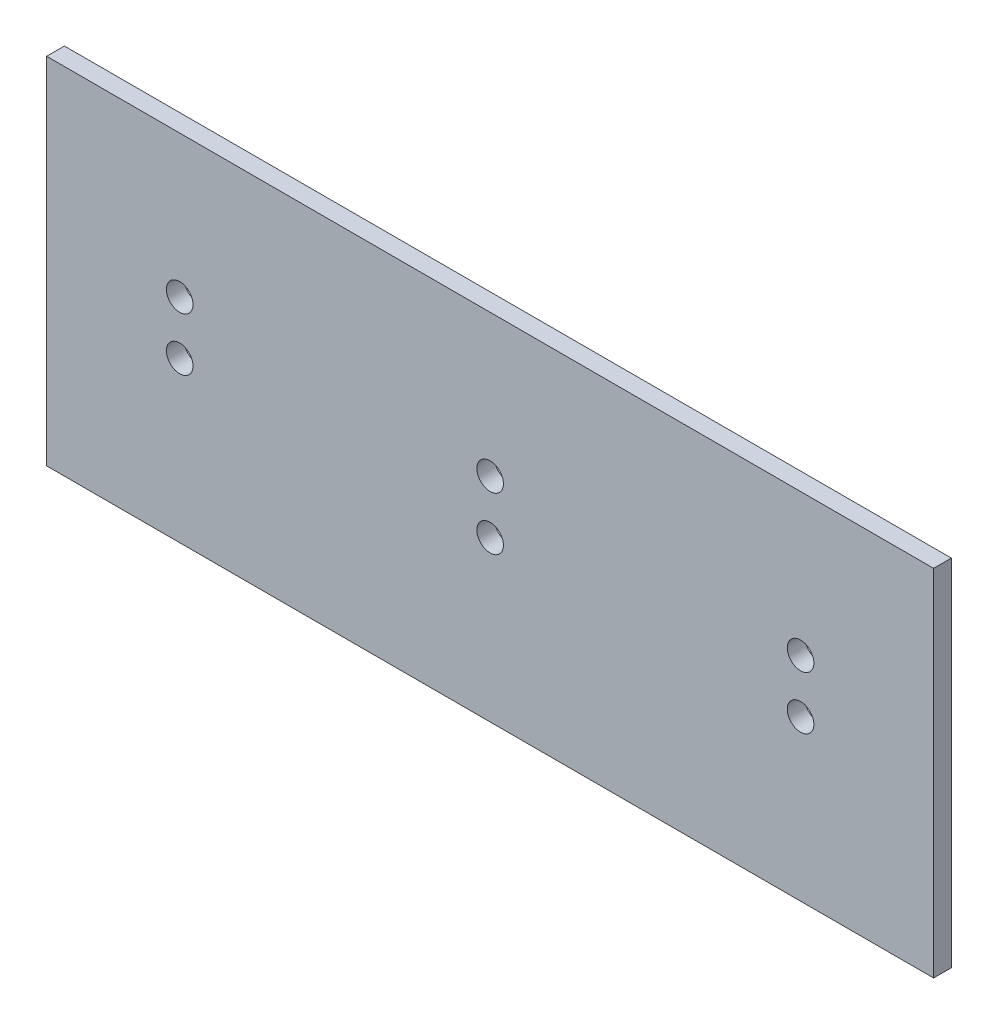
SolidWorks part; units mm, degrees
ref_plane "Front Plane" through (0, 0, 0) normal (0, 0, 1) x (1, 0, 0)
ref_plane "Top Plane" through (0, 0, 0) normal (0, 1, 0) x (1, 0, 0)
ref_plane "Right Plane" through (0, 0, 0) normal (1, 0, 0) x (0, 0, -1)
sketch "Sketch1" plane through (0, 0, 0) normal (0, 0, 1) x (1, 0, 0)
  line L0 (0, 10.7942) -> (0, -9.5057) construction
  line L1 (-50, 20) -> (50, 20)
  line L2 (-50, 20) -> (-50, -20)
  line L3 (-50, -20) -> (50, -20)
  line L4 (50, 20) -> (50, -20)
  line L5 (-50, 20) -> (50, -20) construction
  line L6 (-50, -20) -> (50, 20) construction
  circle A0 centre (-35, -2) radius 1.5
  circle A2 centre (35, 4) radius 1.5
  circle A3 centre (0, 4) radius 1.5
  circle A4 centre (-35, 4) radius 1.5
  circle A5 centre (35, -2) radius 1.5
  circle A6 centre (0, -2) radius 1.5
  point P0 (0, 0)
  point P20 (0, 0)
  point P21 (0, 0)
  dimension "D3" = 24
  dimension "D5" = 3
  dimension "D6" = 3
  dimension "D10" = 3
  dimension "D1" = 40
  dimension "D2" = 100
  dimension "D4" = 18
  dimension "D7" = 35
  dimension "D8" = 35
  dimension "D9" = 24
extrude "Boss-Extrude1" add sketch "Sketch1" along normal blind 2
